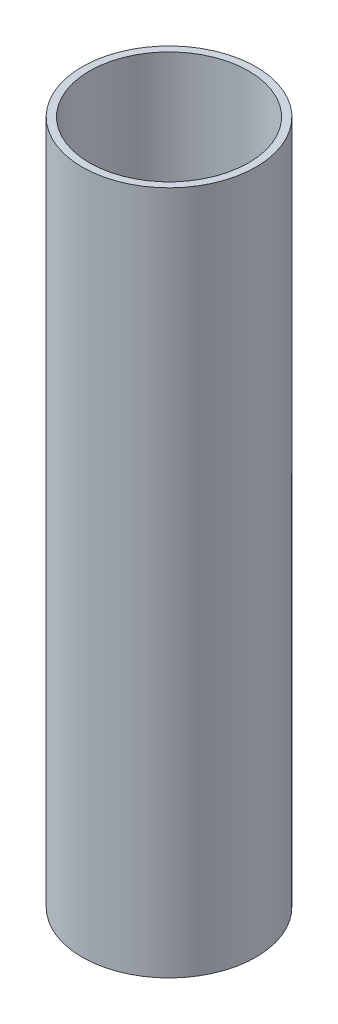
SolidWorks part; units mm, degrees
ref_plane "Front Plane" through (0, 0, 0) normal (0, 0, 1) x (1, 0, 0)
ref_plane "Top Plane" through (0, 0, 0) normal (0, 1, 0) x (1, 0, 0)
ref_plane "Right Plane" through (0, 0, 0) normal (1, 0, 0) x (0, 0, -1)
sketch "Sketch1" plane through (0, 0, 0) normal (0, 1, 0) x (1, 0, 0)
  circle A0 centre (0, 0) radius 19.05
  circle A1 centre (0, 0) radius 17.45
  dimension "D1" = 38.1
  dimension "D2" = 1.6
extrude "Boss-Extrude1" add sketch "Sketch1" along normal blind 150
